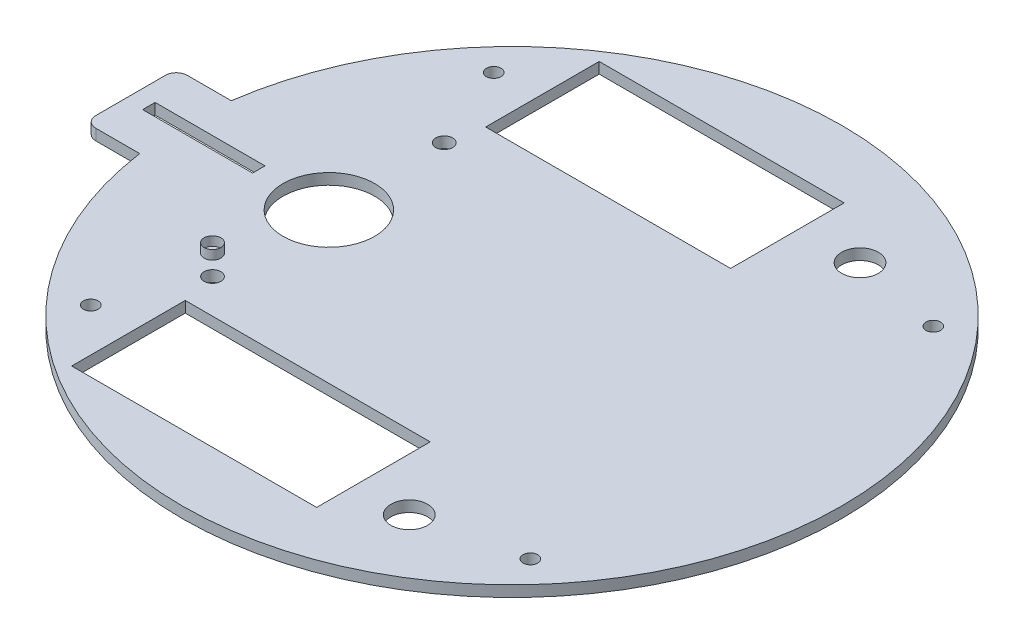
SolidWorks part; units mm, degrees
ref_plane "前基準面" through (0, 0, 0) normal (0, 0, 1) x (1, 0, 0)
ref_plane "上基準面" through (0, 0, 0) normal (0, 1, 0) x (1, 0, 0)
ref_plane "右基準面" through (0, 0, 0) normal (1, 0, 0) x (0, 0, -1)
sketch "草圖2" plane through (0, 0, 0) normal (0, 1, 0) x (1, 0, 0)
  line L1 (-60, 60) -> (60, 60) construction
  line L2 (-60, 60) -> (-60, -60) construction
  line L3 (-60, -60) -> (60, -60) construction
  line L4 (60, 60) -> (60, -60) construction
  line L5 (-60, 60) -> (60, -60) construction
  line L6 (-60, -60) -> (60, 60) construction
  circle A1 centre (0, 0) radius 90
  point P0 (0, 0)
  dimension "D1" = 120
  dimension "D3" = 180
  dimension "D2" = 120
extrude "填料-伸長1" add sketch "草圖2" along normal blind 3
surface "曲面-偏移1" parameters "D1"=0
surface "曲面-偏移2" parameters "D1"=0
sketch "草圖3" plane through (0, 3, 0) normal (0, 1, 0) x (1, 0, 0)
  line L0 (15.6687, 69) -> (15.6687, 44)
  line L1 (-45.2, 44) -> (-45.2, 69)
  line L2 (-45.2, 44) -> (-45.2, 69) construction
  line L3 (15.6687, 69) -> (15.6687, 44) construction
  line L4 (-45.2, -69) -> (-45.2, -44)
  line L5 (15.6687, -44) -> (15.6687, -69)
  line L6 (15.6687, -44) -> (15.6687, -69) construction
  line L7 (-45.2, -69) -> (-45.2, -44) construction
  line L8 (-45.2, 56.5) -> (15.6687, 56.5) construction
  line L9 (-45.2, -56.5) -> (15.6687, -56.5) construction
  line L11 (-48.2, 72) -> (18.6687, 72)
  line L12 (-48.2, 72) -> (-48.2, 41)
  line L13 (-48.2, 41) -> (18.6687, 41)
  line L14 (18.6687, 72) -> (18.6687, 41)
  line L15 (-48.2, 72) -> (18.6687, 41) construction
  line L16 (-48.2, 41) -> (18.6687, 72) construction
  line L17 (-48.2, -41) -> (18.6687, -41)
  line L18 (-48.2, -41) -> (-48.2, -72)
  line L19 (-48.2, -72) -> (18.6687, -72)
  line L20 (18.6687, -41) -> (18.6687, -72)
  line L21 (-48.2, -41) -> (18.6687, -72) construction
  line L22 (-48.2, -72) -> (18.6687, -41) construction
  point P12 (-14.7656, 56.5)
  point P17 (-14.7656, -56.5)
  dimension "D1" = 3
  dimension "D2" = 3
  dimension "D3" = 3
  dimension "D4" = 3
extrude "除料-伸長1" cut sketch "草圖3" against normal blind 3
sketch "草圖4" plane through (0, 3, 0) normal (0, 1, 0) x (1, 0, 0)
  line L0 (0, 0) -> (-50, 0) construction
  circle A1 centre (-50, 0) radius 12.5
  dimension "D2" = 25
  dimension "D1" = 50
extrude "除料-伸長2" cut sketch "草圖4" against normal blind 3
sketch "草圖5" plane through (0, 3, 0) normal (0, 1, 0) x (1, 0, 0)
  line L1 (-60, 55) -> (60, 55) construction
  line L2 (-60, 55) -> (-60, -55) construction
  line L3 (-60, -55) -> (60, -55) construction
  line L4 (60, 55) -> (60, -55) construction
  line L5 (-60, 55) -> (60, -55) construction
  line L6 (-60, -55) -> (60, 55) construction
  circle A0 centre (-60, 55) radius 2
  circle A1 centre (-60, -55) radius 2
  circle A2 centre (60, -55) radius 2
  circle A3 centre (60, 55) radius 2
  point P0 (0, 0)
  dimension "D3" = 4
  dimension "D4" = 4
  dimension "D5" = 4
  dimension "D6" = 4
  dimension "D1" = 120
  dimension "D2" = 110
extrude "除料-伸長3" cut sketch "草圖5" against normal blind 3
sketch "草圖6" plane through (0, 3, 0) normal (0, 1, 0) x (1, 0, 0)
  line L0 (0, 0) -> (126.0142, -2.0364) construction
  circle A0 centre (35, 60) radius 5
  circle A1 centre (33.0431, -61.0996) radius 5
  dimension "D1" = 10
  dimension "D2" = 35
  dimension "D3" = 60
extrude "除料-伸長4" cut sketch "草圖6" against normal blind 10
surface "曲面-偏移3" parameters "D1"=0
sketch "草圖7" plane through (0, 3, 0) normal (0, 1, 0) x (1, 0, 0)
  line L0 (0, 0) -> (-120.1853, 0) construction
  circle A0 centre (-50.1374, -31.6247) radius 2.3 construction
  circle A1 centre (-50.1374, -31.6247) radius 2.3
  circle A2 centre (-50.1374, 31.6247) radius 2.3
extrude "除料-伸長5" cut sketch "草圖7" against normal up to surface (3 mm away) up to face at (35, 0, -55)
sketch "草圖8" plane through (0, 3, 0) normal (0, 1, 0) x (1, 0, 0)
  line L0 (0, 0) -> (-129.4635, 0) construction
  line L2 (-89.1277, 12.5) -> (-101.1277, 12.5)
  line L3 (-89.1277, 12.5) -> (-89.1277, -12.5)
  line L4 (-89.1277, -12.5) -> (-101.1277, -12.5)
  line L5 (-104.1277, 9.5) -> (-104.1277, -9.5)
  circle A0 centre (0, 0) radius 90 construction
  arc A1 (-101.1277, -12.5) -> (-104.1277, -9.5) centre (-101.1277, -9.5) cw
  arc A2 (-101.1277, 12.5) -> (-104.1277, 9.5) centre (-101.1277, 9.5) ccw
  point P9 (0, 0)
  point P10 (0, 0)
  point P13 (-104.1277, -12.5)
  point P16 (-104.1277, 12.5)
  dimension "D3" = 3
  dimension "D1" = 25
  dimension "D2" = 15
extrude "填料-伸長2" add sketch "草圖8" against normal up to surface (3 mm away) up to face at (-50.1374, 0, 33.9247)
sketch "草圖9" plane through (0, 3, 0) normal (0, 1, 0) x (1, 0, 0)
  line L0 (0, 0) -> (-116.8069, 0) construction
  line L1 (-104.1277, 9.5) -> (-104.1277, -9.5) construction
  line L2 (-99.1277, 1.7) -> (-69.1277, 1.7)
  line L3 (-99.1277, 1.7) -> (-99.1277, -1.7)
  line L4 (-99.1277, -1.7) -> (-69.1277, -1.7)
  line L5 (-69.1277, 1.7) -> (-69.1277, -1.7)
  line L6 (-99.1277, 1.7) -> (-69.1277, -1.7) construction
  line L7 (-99.1277, -1.7) -> (-69.1277, 1.7) construction
  point P3 (-84.1277, 0)
  dimension "D1" = 3.4
  dimension "D2" = 30
  dimension "D3" = 5
extrude "除料-伸長6" cut sketch "草圖9" against normal up to surface (3 mm away) up to face at (-50.1374, 0, 33.9247)
